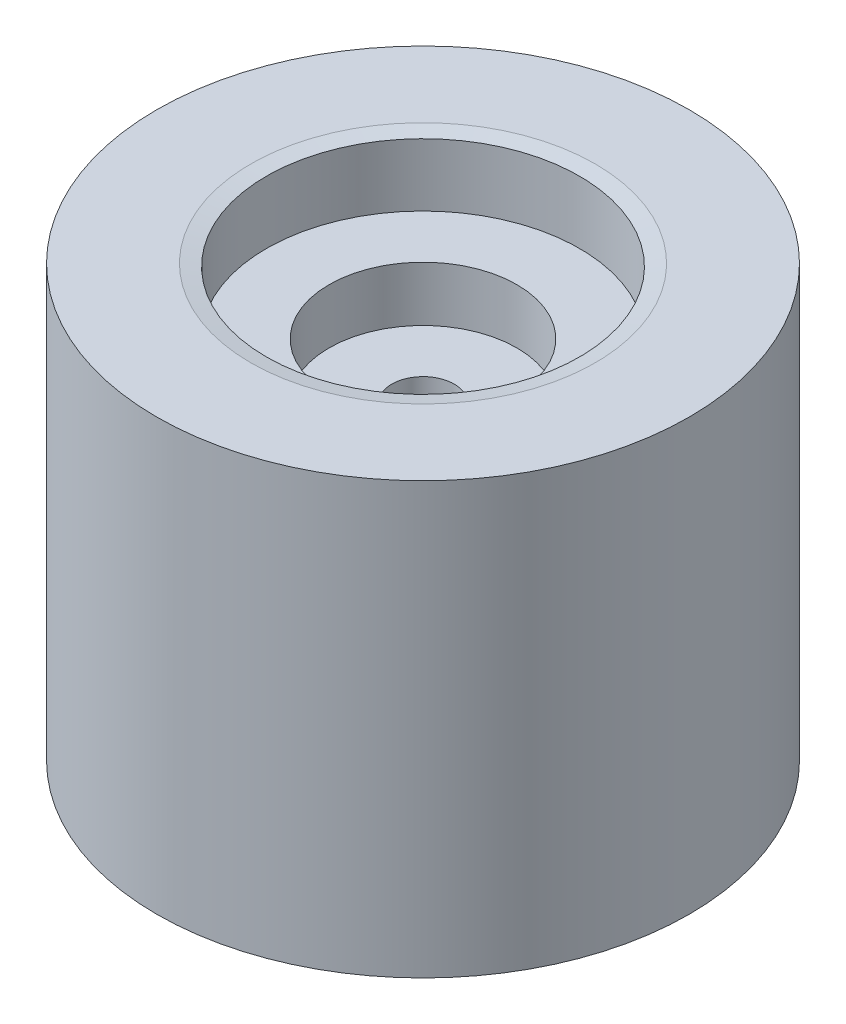
SolidWorks part; units mm, degrees
ref_plane "Front Plane" through (0, 0, 0) normal (0, 0, 1) x (1, 0, 0)
ref_plane "Top Plane" through (0, 0, 0) normal (0, 1, 0) x (1, 0, 0)
ref_plane "Right Plane" through (0, 0, 0) normal (1, 0, 0) x (0, 0, -1)
sketch "Sketch1" plane through (0, 0, 0) normal (0, 0, 1) x (1, 0, 0)
  line L0 (0, 45.8138) -> (0, -41.9093) construction
  line L1 (34, 0) -> (22, 0)
  line L2 (20, 0.3527) -> (22, 0)
  line L3 (12, 8.3527) -> (12, 15.3527)
  line L4 (12, 15.3527) -> (4, 15.3527)
  line L5 (4, 15.3527) -> (4, 39.6473)
  line L6 (4, 39.6473) -> (12, 39.6473)
  line L7 (12, 39.6473) -> (12, 46.6473)
  line L8 (20, 54.6473) -> (22, 55)
  line L9 (22, 55) -> (34, 55)
  line L10 (34, 55) -> (34, 0)
  line L11 (12, 8.3527) -> (20, 8.3527)
  line L12 (20, 8.3527) -> (20, 0.3527)
  line L13 (12, 46.6473) -> (20, 46.6473)
  line L14 (20, 46.6473) -> (20, 54.6473)
  dimension "D1" = 4
  dimension "D2" = 12
  dimension "D3" = 12
  dimension "D4" = 7
  dimension "D5" = 7
  dimension "D6" = 55
  dimension "D7" = 100
  dimension "D8" = 12
  dimension "D9" = 12
  dimension "D10" = 100
  dimension "D11" = 8
  dimension "D12" = 8
  dimension "D13" = 16
  dimension "D14" = 16
  dimension "D15" = 30
revolve "Revolve1" add sketch "Sketch1" angle 360 about L0
sketch "Sketch3" plane through (0, 0, 0) normal (0, -1, 0) x (-1, 0, 0)
  text T0 "Klaver Wheels                          Klaver Wheels                              Klaver Wheels           " font "Century Gothic" height 3.5
extrude "Cut-Extrude2" cut sketch "Sketch3" against normal blind 0.2
